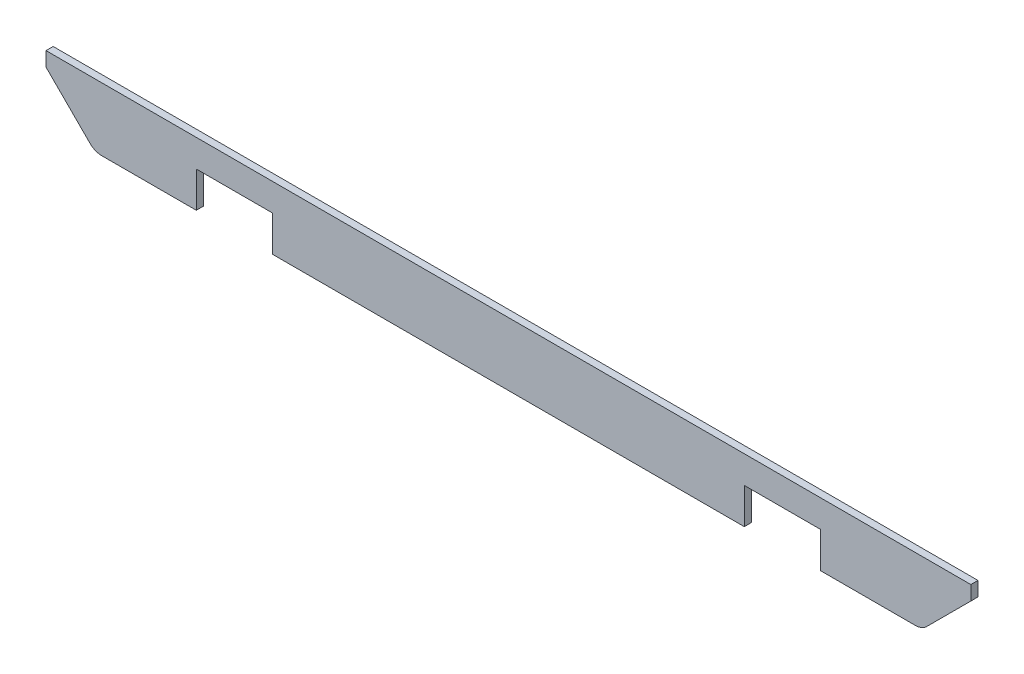
SolidWorks part; units mm, degrees
material "Acrylic (Medium-high impact)"
ref_plane "Front Plane" through (0, 0, 0) normal (0, 0, 1) x (1, 0, 0)
ref_plane "Top Plane" through (0, 0, 0) normal (0, 1, 0) x (1, 0, 0)
ref_plane "Right Plane" through (0, 0, 0) normal (1, 0, 0) x (0, 0, -1)
sketch "Sketch1" plane through (0, 0, 0) normal (0, 0, 1) x (1, 0, 0)
  line L0 (0, -986.749) -> (0, 49013.251) construction
  line L1 (130.9553, -26.5) -> (170.4338, -26.5)
  line L3 (0, 0) -> (0, -26.5)
  line L4 (-98.9553, -26.5) -> (98.9553, -26.5)
  line L5 (194, -6) -> (175.3836, -24.6164)
  line L6 (194, -6) -> (194, 0)
  line L7 (98.9553, -26.5) -> (98.9553, -11.5)
  line L8 (98.9553, -11.5) -> (130.9553, -11.5)
  line L9 (130.9553, -26.5) -> (130.9553, -11.5)
  line L10 (-130.9553, -26.5) -> (-130.9553, -11.5)
  line L11 (-98.9553, -11.5) -> (-130.9553, -11.5)
  line L12 (-98.9553, -26.5) -> (-98.9553, -11.5)
  line L13 (-194, -6) -> (-194, 0)
  line L14 (-194, -6) -> (-175.3836, -24.6164)
  line L15 (-130.9553, -26.5) -> (-170.4338, -26.5)
  line L21 (194, 0) -> (-194, 0)
  arc A0 (-170.4338, -26.5) -> (-175.3836, -24.6164) centre (-170.6041, -19.5021) cw
  arc A1 (170.4338, -26.5) -> (175.3836, -24.6164) centre (170.6041, -19.5021) ccw
  point P10 (194, -3)
  point P11 (0, -13.25)
  point P25 (0, 0)
  point P26 (0, 0)
  dimension "D7" = 7
  dimension "D1" = 6
  dimension "D2" = 26.5
  dimension "D3" = 6.9979
  dimension "D4" = 26.3276
  dimension "D5" = 23.3959
  dimension "D6" = 170.6041
  dimension "D8" = 32
  dimension "D9" = 15
  dimension "D10" = 71.6488
extrude "Boss-Extrude1" add sketch "Sketch1" along normal blind 3
